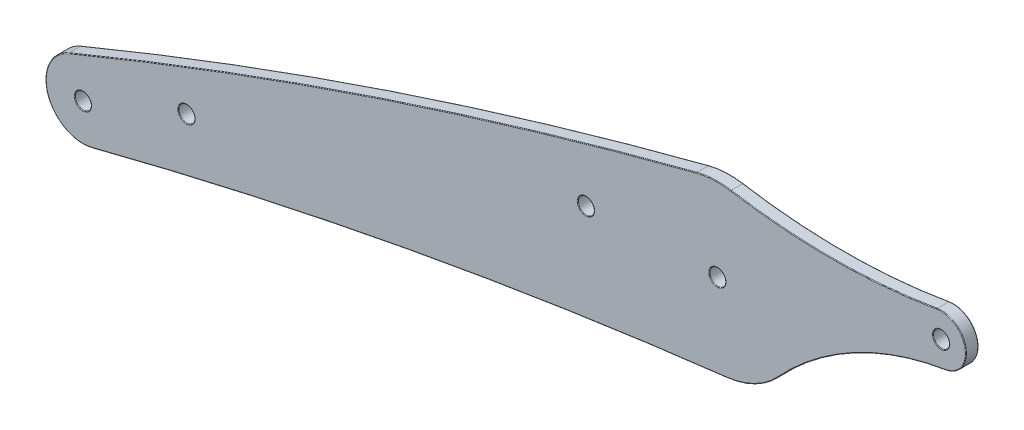
SolidWorks part; units mm, degrees
ref_plane "Front Plane" through (0, 0, 0) normal (0, 0, 1) x (1, 0, 0)
ref_plane "Top Plane" through (0, 0, 0) normal (0, 1, 0) x (1, 0, 0)
ref_plane "Right Plane" through (0, 0, 0) normal (1, 0, 0) x (0, 0, -1)
sketch "Sketch1" plane through (0, 0, 0) normal (0, 0, 1) x (1, 0, 0)
  line L0 (-177.9916, 165.7696) -> (29.1483, 219.5198) construction
  line L1 (-177.9916, 165.7696) -> (29.1483, 219.5198) construction
  point P0 (-24.8517, 205.5075)
sketch "Sketch2" plane through (0, 0, 0) normal (0, 0, 1) x (1, 0, 0)
  circle A0 centre (-177.9916, 165.7696) radius 9 construction
  circle A1 centre (-24.8517, 205.5075) radius 10 construction
  circle A2 centre (-24.8517, 205.5075) radius 20 construction
  circle A3 centre (29.1483, 219.5198) radius 6 construction
  arc A4 (-29.8724, 224.8671) -> (-181.437, 174.084) centre (258.8168, -888.3079) ccw
  arc A5 (-175.745, 157.0545) -> (-22.5241, 185.6434) centre (111.3142, -956.5419) cw
  arc A6 (-21.6108, 225.2432) -> (28.1309, 225.4329) centre (2.6957, 373.2607) ccw
  arc A7 (-10.1479, 191.9503) -> (30.1089, 213.5972) centre (41.3155, 144.5001) cw
  arc A8 (-29.8724, 224.8671) -> (-21.6108, 225.2432) centre (-24.8517, 205.5075) cw
  arc A9 (-22.5241, 185.6434) -> (-10.1479, 191.9503) centre (-24.8517, 205.5075) ccw
  arc A10 (28.1309, 225.4329) -> (30.1089, 213.5972) centre (29.1483, 219.5198) cw
  arc A11 (-181.437, 174.084) -> (-175.745, 157.0545) centre (-177.9916, 165.7696) ccw
  arc A12 (-177.9916, 165.7696) -> (29.1483, 219.5198) centre (122.1736, -564.984) cw construction
  point P27 (-152.9916, 175.5456)
  point P28 (-56.5865, 204.5255)
  dimension "D1" = 18
  dimension "D2" = 40
  dimension "D3" = 20
  dimension "D4" = 12
  dimension "D5" = 1150
  dimension "D6" = 1150
  dimension "D7" = 70
  dimension "D8" = 150
  dimension "D9" = 790
  dimension "D10" = 31.75
  dimension "D11" = 25
extrude "Boss-Extrude1" add sketch "Sketch2" against normal blind 3
hole_wizard "M3.5 Clearance Hole1" positions "Sketch5" profile "Sketch6" hole size "M3.5" standard "ISO" end condition up to next
sketch "Sketch5" plane through (0, 0, 0) normal (0, 0, 1) x (1, 0, 0)
  point P0 (-177.9916, 165.7696)
  point P3 (-152.9916, 175.5456)
  point P6 (-56.5865, 204.5255)
  point P9 (-24.8517, 205.5075)
  point P12 (29.1483, 219.5198)
sketch "Sketch6" plane through (-177.9916, 165.7696, 0) normal (1, 0, 0) x (0, -1, 0)
  line L0 (0, 0) -> (0, 3)
  line L1 (0, 3) -> (1.95, 3)
  line L2 (1.95, 3) -> (1.95, 0)
  line L5 (1.95, 0) -> (0, 0)
  line L11 (0, -6.35) -> (0, 107.95) construction
  dimension "Thru Hole Dia." = 3.9
  dimension "Thru Hole Depth" = 3
fillet "Fillet1" radius 0.15 26 edges at (-106.5381, 202.1121, -3) (-186.5274, 162.9166, -3) (-99.6195, 173.9478, -3) (-15.7709, 187.6879, -3) (8.1639, 206.1521, -3) (35.0662, 220.5088, -3) (3.2679, 223.2618, -3) (-25.7613, 225.4868, -3) (27.1983, 219.5198, -3) (-26.8017, 205.5075, -3) (-58.5365, 204.5255, -3) (-154.9416, 175.5456, -3) (-179.9416, 165.7696, -3) (-176.0416, 165.7696, 0) (-151.0416, 175.5456, 0) (-54.6365, 204.5255, 0) (-22.9017, 205.5075, 0) (31.0983, 219.5198, 0) (3.2679, 223.2618, 0) (35.0662, 220.5088, 0) (8.1639, 206.1521, 0) (-15.7709, 187.6879, 0) (-99.6195, 173.9478, 0) (-186.5274, 162.9166, 0) (-106.5381, 202.1121, 0) (-25.7613, 225.4868, 0)
